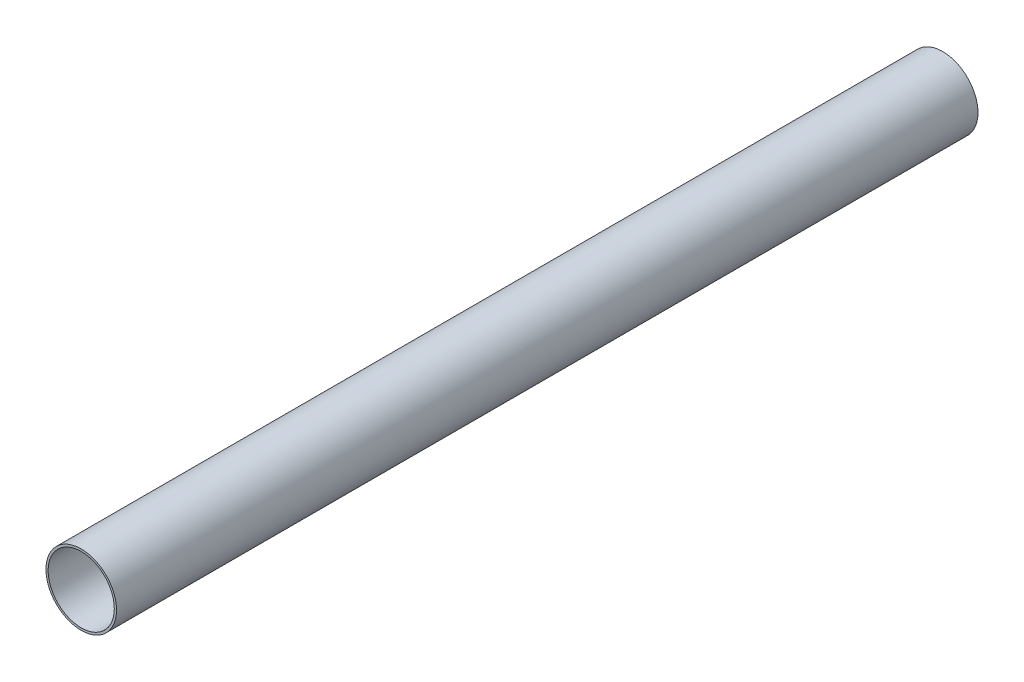
SolidWorks part; units mm, degrees
material "EPDM 60 Durometer"
ref_plane "Front Plane" through (0, 0, 0) normal (0, 0, 1) x (1, 0, 0)
ref_plane "Top Plane" through (0, 0, 0) normal (0, 1, 0) x (1, 0, 0)
ref_plane "Right Plane" through (0, 0, 0) normal (1, 0, 0) x (0, 0, -1)
sketch "Sketch1" plane through (0, 0, 0) normal (0, 0, 1) x (1, 0, 0)
  circle A0 centre (0, 0) radius 50.8381
  circle A1 centre (0, 0) radius 47.6631
  dimension "D1" = 101.6762
  dimension "D2" = 3.175
extrude "Boss-Extrude1" add sketch "Sketch1" along normal blind 1241.2726
